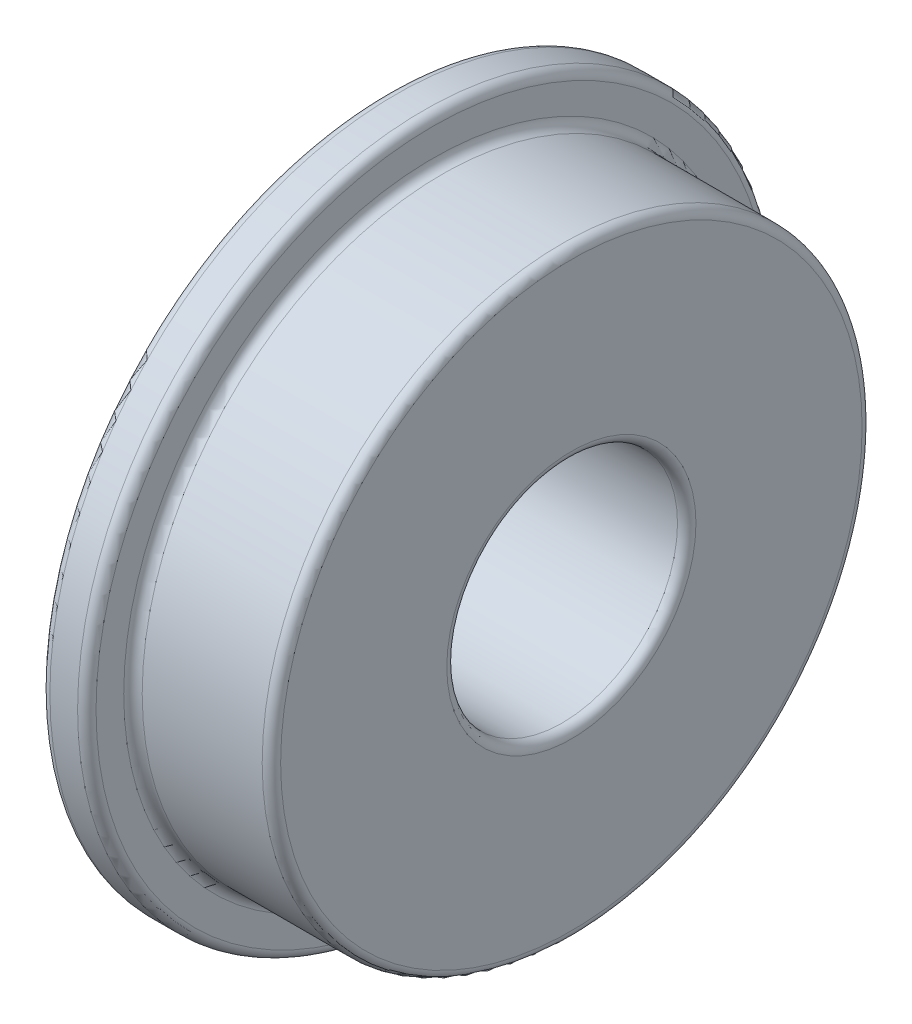
SolidWorks part; units mm, degrees
ref_plane "Front Plane" through (0, 0, 0) normal (0, 0, 1) x (1, 0, 0)
ref_plane "Top Plane" through (0, 0, 0) normal (0, 1, 0) x (1, 0, 0)
ref_plane "Right Plane" through (0, 0, 0) normal (1, 0, 0) x (0, 0, -1)
sketch "Main Revolve Sketch" plane through (0, 0, 0) normal (0, 0, 1) x (1, 0, 0)
  line L0 (0, 2.5) -> (4, 2.5)
  line L1 (4, 2.5) -> (4, 6.5)
  line L2 (4, 6.5) -> (1, 6.5)
  line L3 (1, 6.5) -> (1, 7.5)
  line L4 (1, 7.5) -> (0, 7.5)
  line L5 (0, 7.5) -> (0, 2.5)
  line L6 (0, 0) -> (5.3309, 0) construction
  dimension "D1" = 2.5
  dimension "D2" = 7.5
  dimension "D3" = 6.5
  dimension "D4" = 4
  dimension "D5" = 1
revolve "Main Revolve" add sketch "Main Revolve Sketch" angle 360 about L6
fillet "Fillet1" radius 0.2 6 edges at (0, 0, 7.5) (0, 0, 2.5) (4, 0, 2.5) (1, 0, 6.5) (4, 0, 6.5) (1, 0, 7.5)
